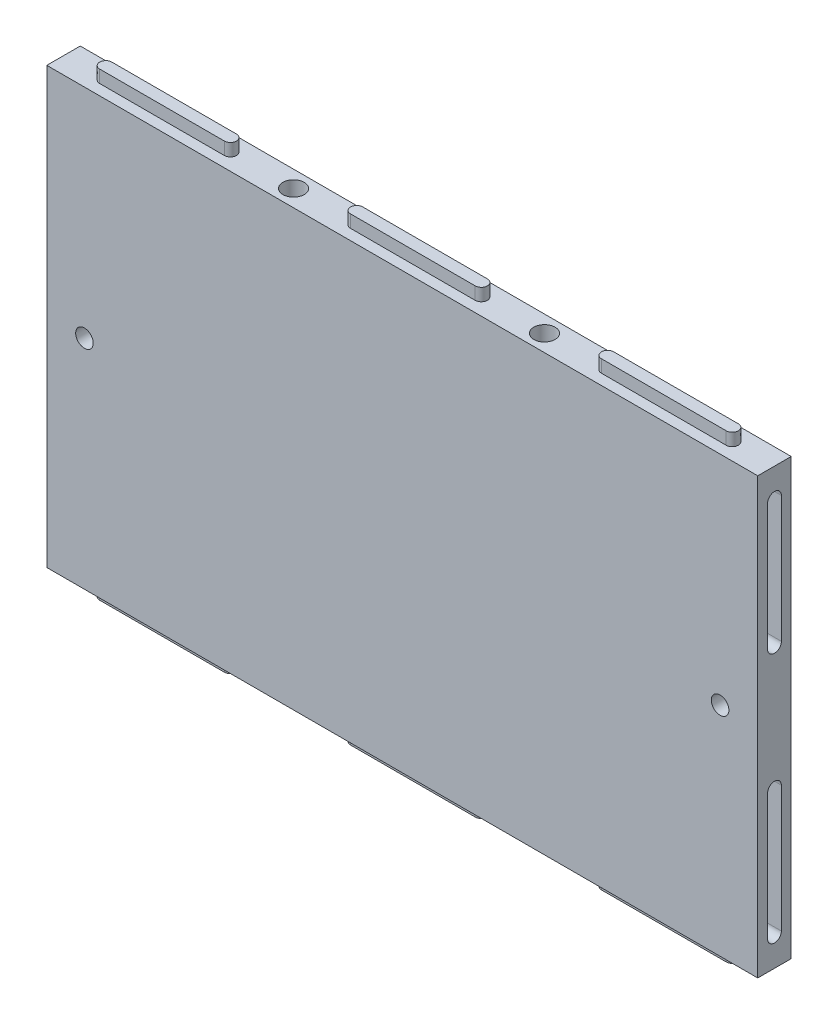
SolidWorks part; units mm, degrees
ref_plane "Ön Düzlem" through (0, 0, 0) normal (0, 0, 1) x (1, 0, 0)
ref_plane "Üst Düzlem" through (0, 0, 0) normal (0, 1, 0) x (1, 0, 0)
ref_plane "Sağ Düzlem" through (0, 0, 0) normal (1, 0, 0) x (0, 0, -1)
sketch "Çizim1" plane through (0, 0, 0) normal (0, 0, 1) x (1, 0, 0)
  line L1 (-85, 52) -> (85, 52)
  line L2 (-85, 52) -> (-85, -52)
  line L3 (-85, -52) -> (85, -52)
  line L4 (85, 52) -> (85, -52)
  line L5 (-85, 52) -> (85, -52) construction
  line L6 (-85, -52) -> (85, 52) construction
  point P0 (0, 0)
  dimension "D1" = 104
  dimension "D2" = 170
extrude "Yükseklik-Ekstrüzyon1" add sketch "Çizim1" along normal mid plane 8
sketch "Çizim2" plane through (0, 0, 0) normal (0, 1, 0) x (1, 0, 0)
  line L0 (-74.9, 0) -> (-45.1, 0) construction
  line L1 (-74.9, 1.45) -> (-45.1, 1.45)
  line L2 (-74.9, -1.45) -> (-45.1, -1.45)
  line L3 (-14.9, 0) -> (14.9, 0) construction
  line L4 (-14.9, 1.45) -> (14.9, 1.45)
  line L5 (-14.9, -1.45) -> (14.9, -1.45)
  line L6 (45.1, 0) -> (74.9, 0) construction
  line L7 (45.1, 1.45) -> (74.9, 1.45)
  line L8 (45.1, -1.45) -> (74.9, -1.45)
  line L9 (-85, -4) -> (-85, 4) construction
  line L10 (-60, 0) -> (0, 0) construction
  line L11 (0, 0) -> (60, 0) construction
  arc A0 (-74.9, 1.45) -> (-74.9, -1.45) centre (-74.9, 0) ccw
  arc A1 (-45.1, -1.45) -> (-45.1, 1.45) centre (-45.1, 0) ccw
  arc A2 (-14.9, 1.45) -> (-14.9, -1.45) centre (-14.9, 0) ccw
  arc A3 (14.9, -1.45) -> (14.9, 1.45) centre (14.9, 0) ccw
  arc A4 (45.1, 1.45) -> (45.1, -1.45) centre (45.1, 0) ccw
  arc A5 (74.9, -1.45) -> (74.9, 1.45) centre (74.9, 0) ccw
  point P2 (-60, 0)
  point P8 (0, 0)
  point P15 (60, 0)
  point P24 (-85, 0)
  dimension "D2" = 1.45
  dimension "D1" = 29.8
  dimension "D3" = 25
extrude "Yükseklik-Ekstrüzyon2" add sketch "Çizim2" along normal mid plane 110
sketch "Çizim3" plane through (0, 52, 0) normal (0, 1, 0) x (1, 0, 0)
  line L0 (-60, 1.45) -> (0, 1.45) construction
  line L1 (-45.1, 1.45) -> (-74.9, 1.45) construction
  line L2 (14.9, 1.45) -> (-14.9, 1.45) construction
  line L3 (0, -1.45) -> (60, -1.45) construction
  line L4 (-14.9, -1.45) -> (14.9, -1.45) construction
  line L5 (45.1, -1.45) -> (74.9, -1.45) construction
  circle A0 centre (-30, 0) radius 2.55
  circle A1 centre (30, 0) radius 2.55
  point P4 (30, -1.45)
  point P12 (-30, 1.45)
  dimension "D1" = 5.1
extrude "Kes-Ekstrüzyon1" cut sketch "Çizim3" against normal blind 12
mirror "Aynalama1" about plane through (0, 0, 0) normal (0, 1, 0) of "Kes-Ekstrüzyon1"
sketch "Çizim4" plane through (-85, 0, 0) normal (-1, 0, 0) x (0, 0, 1)
  line L0 (0, -45.1) -> (0, -14.9) construction
  line L1 (-1.65, -45.1) -> (-1.65, -14.9)
  line L2 (1.65, -45.1) -> (1.65, -14.9)
  line L3 (0, 14.9) -> (0, 45.1) construction
  line L4 (-1.65, 14.9) -> (-1.65, 45.1)
  line L5 (1.65, 14.9) -> (1.65, 45.1)
  line L6 (0, -30) -> (0, 30) construction
  line L7 (4, 52) -> (4, -52) construction
  line L8 (4, 52) -> (-4, 52) construction
  arc A0 (-1.65, -45.1) -> (1.65, -45.1) centre (0, -45.1) ccw
  arc A1 (1.65, -14.9) -> (-1.65, -14.9) centre (0, -14.9) ccw
  arc A2 (-1.65, 14.9) -> (1.65, 14.9) centre (0, 14.9) ccw
  arc A3 (1.65, 45.1) -> (-1.65, 45.1) centre (0, 45.1) ccw
  point P2 (0, -30)
  point P8 (0, 30)
  point P16 (0, 0)
  point P19 (4, 0)
  dimension "D1" = 1.65
  dimension "D2" = 30.2
  dimension "D3" = 22
extrude "Kes-Ekstrüzyon2" cut sketch "Çizim4" against normal blind 7
sketch "Çizim5" plane through (0, 0, 0) normal (0, 0, 1) x (1, 0, 0)
  line L0 (-85, 52) -> (-85, -52) construction
  circle A0 centre (-76, 0) radius 2.1
  point P6 (-85, 0)
  dimension "D1" = 4.2
  dimension "D2" = 9
extrude "Kes-Ekstrüzyon3" cut sketch "Çizim5" against normal mid plane 10
sketch "Çizim7" plane through (0, 0, -4) normal (0, 0, -1) x (-1, 0, 0)
  circle A0 centre (76, 0) radius 4.4
  circle A1 centre (76, 0) radius 2.1 construction
  dimension "D1" = 8.8
extrude "Kes-Ekstrüzyon5" cut sketch "Çizim7" against normal blind 3.5
mirror "Aynalama2" about plane through (0, 0, 0) normal (1, 0, 0) of "Kes-Ekstrüzyon2", "Kes-Ekstrüzyon3", "Kes-Ekstrüzyon5"
